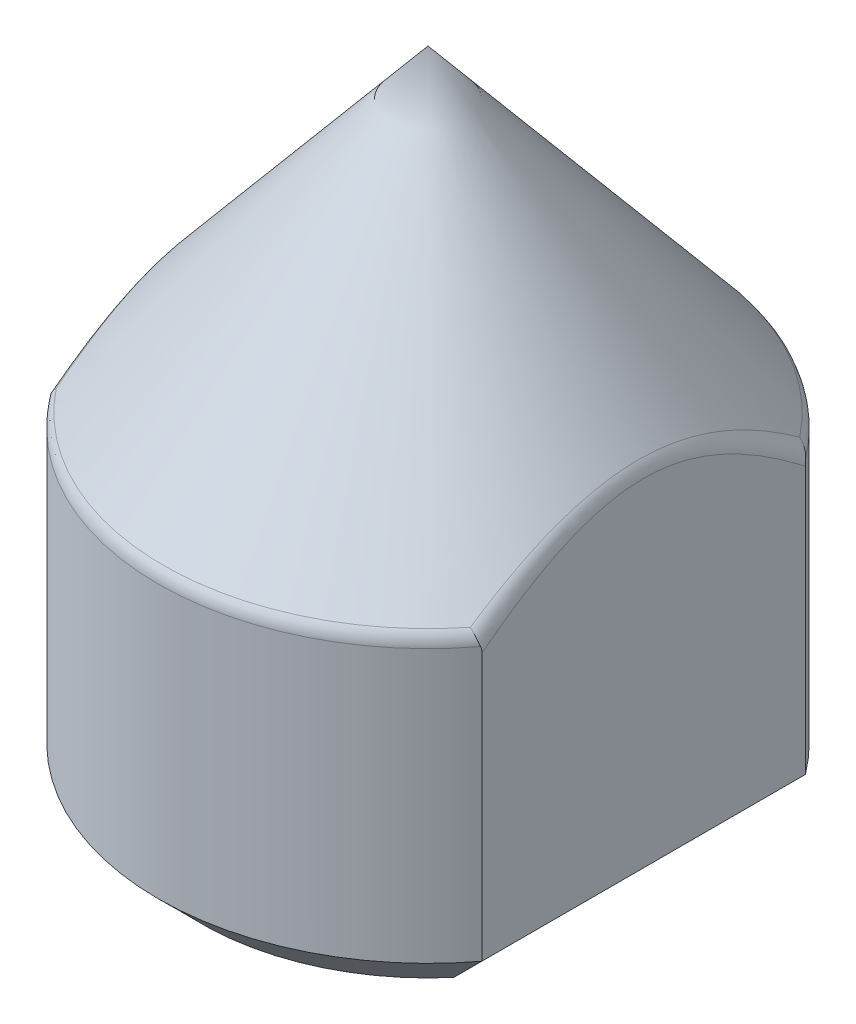
SolidWorks part; units mm, degrees
material "Custom Plastic"
ref_plane "Front Plane" through (0, 0, 0) normal (0, 0, 1) x (1, 0, 0)
ref_plane "Top Plane" through (0, 0, 0) normal (0, 1, 0) x (1, 0, 0)
ref_plane "Right Plane" through (0, 0, 0) normal (1, 0, 0) x (0, 0, -1)
sketch "Sketch1" plane through (0, 0, 0) normal (0, 1, 0) x (1, 0, 0)
  circle A0 centre (0, 0) radius 12.5
  dimension "D1" = 25
extrude "Boss-Extrude2" add sketch "Sketch1" along normal blind 15 contours A0
sketch "Sketch2" plane through (0, 0, 0) normal (0, 0, 1) x (1, 0, 0)
  line L0 (0, -1000) -> (0, 49000) construction
  line L1 (-12.5, 0) -> (12.5, 0) construction
  line L2 (12.5, 15) -> (0, 30)
  line L3 (0, 30) -> (0, 15)
  line L4 (12.5, 15) -> (-12.5, 15) construction
  line L5 (0, 15) -> (12.5, 15)
  point P5 (0, 0)
  dimension "D1" = 15
revolve "Revolve1" add sketch "Sketch2" angle 360 about L0
sketch "Sketch3" plane through (0, 0, 0) normal (0, 1, 0) x (1, 0, 0)
  line L0 (0, -1000) -> (0, 49000) construction
  line L1 (-10, 7.5) -> (-10, -7.5)
  line L2 (10, 7.5) -> (10, -7.5)
  circle A0 centre (0, 0) radius 12.5 construction
  arc A1 (-10, 7.5) -> (-10, -7.5) centre (0, 0) ccw
  arc A2 (10, -7.5) -> (10, 7.5) centre (0, 0) ccw
  point P2 (0, 0)
  point P9 (0, 0)
  point P10 (0, 0)
  point P11 (0, 0)
  point P12 (0, 0)
  point P13 (0, 0)
  point P14 (0, 0)
  dimension "D1" = 20
extrude "Cut-Extrude1" cut sketch "Sketch3" along normal up to next
chamfer "Chamfer1" distance 2 angle 45 4 edges at (0, 0, -12.5) (0, 0, 12.5) (10, 0, 0) (-10, 0, 0)
fillet "Fillet1" radius 1 4 edges at (10, 17.929, -1.0897) (0, 15, -12.5) (0, 15, 12.5) (-10, 17.929, 1.0897)
